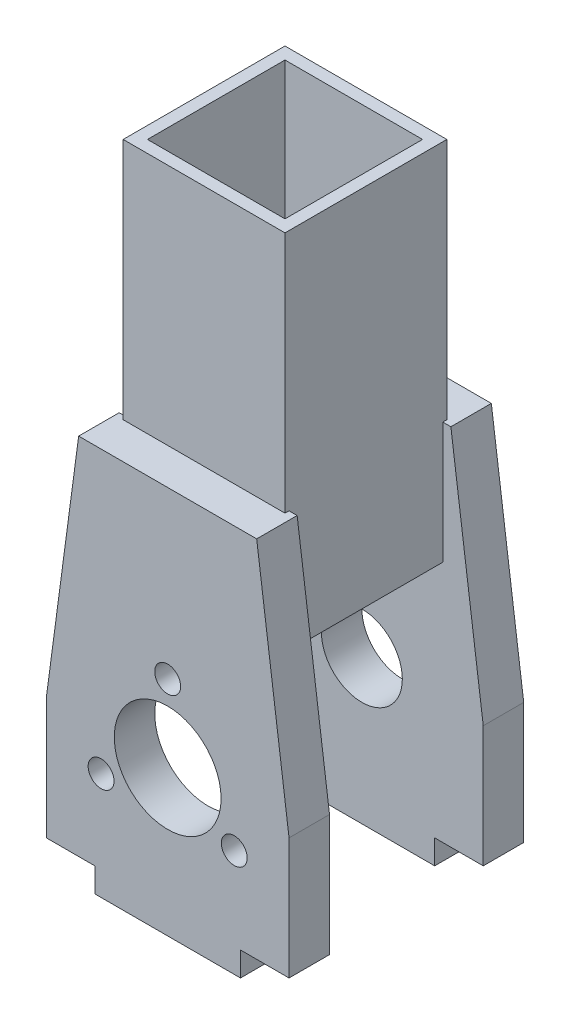
SolidWorks part; units mm, degrees
ref_plane "正面" through (0, 0, 0) normal (0, 0, 1) x (1, 0, 0)
ref_plane "平面" through (0, 0, 0) normal (0, 1, 0) x (1, 0, 0)
ref_plane "右側面" through (0, 0, 0) normal (1, 0, 0) x (0, 0, -1)
sketch "shoulder_roll_connection_sketch" plane through (0, 0, 0) normal (0, 1, 0) x (1, 0, 0)
  circle A0 centre (0, 0) radius 27.5 construction
  circle A1 centre (0, 0) radius 22.5 construction
  circle A2 centre (0, 22.5) radius 1.6 construction
  circle A3 centre (-22.5, 0) radius 1.6 construction
  circle A4 centre (22.5, 0) radius 1.6 construction
  circle A5 centre (0, -22.5) radius 1.6 construction
  dimension "D1" = 55
  dimension "D2" = 45
  dimension "D3" = 3.2
ref_plane "shoulder_yaw_m2006_mount_surface" through (0, 0, 9.5) normal (0, 0, 1) x (1, 0, 0)
ref_plane "shoulder_yaw_m2006_axis_hold_mount_surface" through (0, 0, -9.5) normal (0, 0, 1) x (1, 0, 0)
sketch "ｽｹｯﾁ4" plane through (0, 0, 9.5) normal (0, 0, 1) x (1, 0, 0)
  line L0 (-15, 0) -> (-9, 0)
  line L1 (-9, 0) -> (-9, -3)
  line L8 (-11, 45) -> (-15, 15)
  line L9 (-15, 15) -> (-15, 0)
  line L10 (0, 0) -> (0, 45) construction
  line L11 (-11, 45) -> (11, 45)
  line L12 (-9, -3) -> (9, -3)
  line L13 (15, 0) -> (9, 0)
  line L14 (15, 15) -> (15, 0)
  line L15 (11, 45) -> (15, 15)
  line L16 (9, 0) -> (9, -3)
  circle A0 centre (0, 15) radius 12.5 construction
  circle A1 centre (0, 15) radius 6.6
  circle A2 centre (0, 15) radius 9.5 construction
  circle A3 centre (0, 24.5) radius 1.6
  circle A5 centre (8.2272, 10.25) radius 1.6
  circle A6 centre (-8.2272, 10.25) radius 1.6
  point P15 (0, -3)
  point P22 (0, 15)
  dimension "D3" = 25
  dimension "D5" = 13.2
  dimension "D6" = 19
  dimension "D7" = 3
  dimension "D8" = 3.2
  dimension "D1" = 3
  dimension "D2" = 15
  dimension "D4" = 15
  dimension "D9" = 15
  dimension "D10" = 30
  dimension "D11" = 11
  dimension "D12" = 6
extrude "ﾎﾞｽ - 押し出し1" add sketch "ｽｹｯﾁ4" along normal blind 5
sketch "ｽｹｯﾁ7" plane through (0, 0, -9.5) normal (0, 0, 1) x (1, 0, 0)
  line L0 (15, 0) -> (9, 0)
  line L1 (9, 0) -> (9, -3)
  line L2 (9, -3) -> (-9, -3)
  line L3 (0, -3) -> (0, 45) construction
  line L4 (-11, 45) -> (11, 45)
  line L5 (11, 45) -> (15, 15)
  line L6 (15, 15) -> (15, 0)
  line L7 (37.4, 0) -> (-37.4, 0) construction
  line L8 (-15, 15) -> (-15, 0)
  line L9 (-11, 45) -> (-15, 15)
  line L10 (-9, 0) -> (-9, -3)
  line L11 (-15, 0) -> (-9, 0)
  circle A0 centre (0, 15) radius 5
  circle A1 centre (0, 15) radius 6.6 construction
  dimension "D7" = 10
  dimension "D1" = 11
  dimension "D2" = 15
  dimension "D3" = 3
  dimension "D4" = 6
  dimension "D5" = 30
  dimension "D6" = 45
extrude "ﾎﾞｽ - 押し出し2" add sketch "ｽｹｯﾁ7" against normal blind 5 separate body
sketch "ｽｹｯﾁ8" plane through (0, 45, 0) normal (0, 1, 0) x (1, 0, 0)
  line L0 (-8.5, -8.5) -> (8.5, -8.5)
  line L1 (-10, 10) -> (10, 10)
  line L2 (-10, 10) -> (-10, -10)
  line L3 (-10, -10) -> (10, -10)
  line L4 (10, 10) -> (10, -10)
  line L5 (-10, 10) -> (10, -10) construction
  line L6 (-10, -10) -> (10, 10) construction
  line L7 (8.5, 8.5) -> (8.5, -8.5)
  line L8 (-8.5, 8.5) -> (8.5, 8.5)
  line L9 (-8.5, 8.5) -> (-8.5, -8.5)
  point P0 (0, 0)
  dimension "D1" = 20
  dimension "D2" = 20
  dimension "D3" = 1.5
extrude "ﾎﾞｽ - 押し出し3" add sketch "ｽｹｯﾁ8" against normal blind 15 and the other way blind 30 separate body
